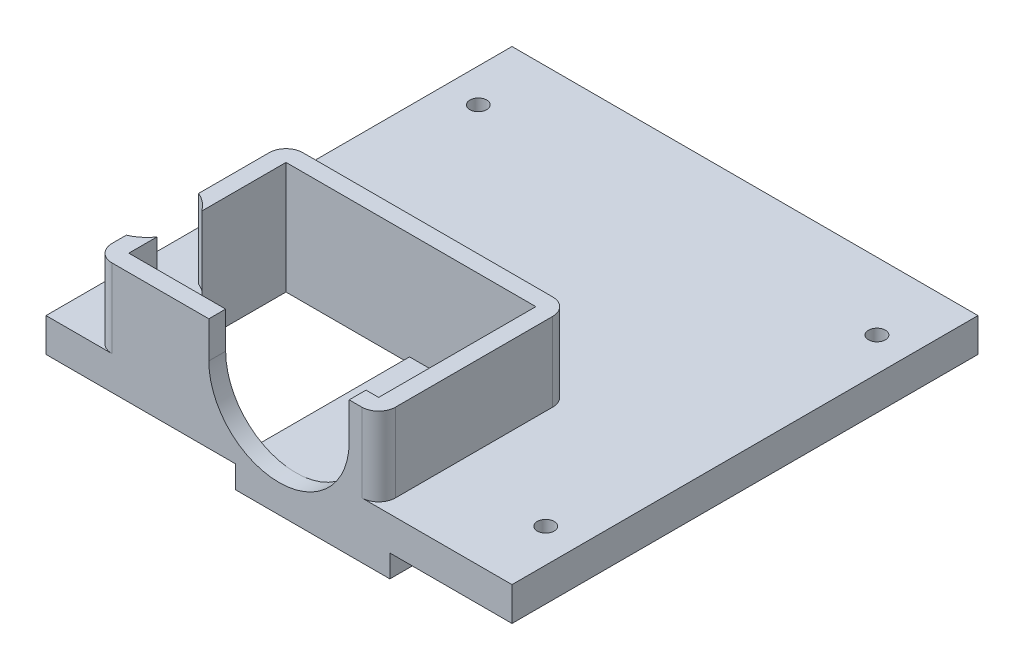
SolidWorks part; units mm, degrees
material "PVB"
ref_plane "Front Plane" through (0, 0, 0) normal (0, 0, 1) x (1, 0, 0)
ref_plane "Top Plane" through (0, 0, 0) normal (0, 1, 0) x (1, 0, 0)
ref_plane "Right Plane" through (0, 0, 0) normal (1, 0, 0) x (0, 0, -1)
sketch "Sketch1" plane through (0, 0, 0) normal (0, 1, 0) x (1, 0, 0)
  line L1 (0, 0) -> (83, 0)
  line L2 (0, 0) -> (0, 83)
  line L3 (0, 83) -> (83, 83)
  line L4 (83, 0) -> (83, 83)
  dimension "D1" = 83
  dimension "D2" = 83
extrude "Boss-Extrude1" add sketch "Sketch1" along normal blind 6
sketch "Sketch2" plane through (0, 6, 0) normal (0, 1, 0) x (1, 0, 0)
  line L0 (83, 83) -> (0, 83) construction
  line L1 (0, 83) -> (0, 0) construction
  line L2 (0, 0) -> (83, 0) construction
  line L3 (83, 0) -> (83, 83) construction
  circle A0 centre (6, 71) radius 1.5
  circle A1 centre (6, 12) radius 1.5
  circle A2 centre (77, 12) radius 1.5
  circle A3 centre (77, 71) radius 1.5
  dimension "D1" = 3
  dimension "D2" = 3
  dimension "D3" = 3
  dimension "D4" = 3
  dimension "D6" = 6
  dimension "D7" = 12
  dimension "D8" = 6
  dimension "D9" = 6
  dimension "D10" = 12
  dimension "D11" = 6
  dimension "D5" = 12
  dimension "D12" = 12
extrude "Cut-Extrude1" cut sketch "Sketch2" against normal through all
ref_plane "Plane1" through (0, 0, -41.5) normal (0, 0, 1) x (1, 0, 0)
sketch "Sketch4" plane through (0, 6, 0) normal (0, 1, 0) x (1, 0, 0)
  line L0 (3, 21) -> (3, 9)
  line L1 (3, 9) -> (13, 9)
  line L2 (13, 15) -> (8, 21)
  line L3 (3, 21) -> (8, 21)
  line L4 (8, 21) -> (13, 15)
  line L5 (13, 15) -> (13, 9)
  line L6 (0, 83) -> (0, 0) construction
  line L7 (0, 0) -> (83, 0) construction
  circle A0 centre (6, 12) radius 1.5
  circle A1 centre (6, 12) radius 1.5 construction
  dimension "D1" = 3
  dimension "D2" = 9
  dimension "D3" = 12
  dimension "D4" = 10
  dimension "D5" = 6
  dimension "D6" = 5
ref_plane "Plane2" through (41.5, 0, 0) normal (-1, 0, 0) x (0, 0, 1)
sketch "Sketch5" plane through (0, 6, 0) normal (0, 1, 0) x (1, 0, 0)
  line L0 (8.75, 34) -> (8.75, 0)
  line L1 (8.75, 34) -> (59.25, 34)
  line L2 (8.75, 0) -> (59.25, 0)
  line L3 (59.25, 34) -> (59.25, 0)
  line L4 (8.75, 34) -> (59.25, 0) construction
  line L5 (8.75, 0) -> (59.25, 34) construction
  line L6 (41.5, 3.3) -> (41.5, -3.3) construction
  line L12 (0, 0) -> (83, 0) construction
  point P1 (34, 17)
  dimension "D1" = 50.5
  dimension "D2" = 34
  dimension "D3" = 7.5
extrude "Boss-Extrude2" add sketch "Sketch5" along normal blind 22
sketch "Sketch6" plane through (0, 28, 0) normal (0, 1, 0) x (1, 0, 0)
  line L14 (56.25, 31) -> (11.75, 31)
  line L15 (11.75, 31) -> (11.75, 3)
  line L16 (11.75, 3) -> (56.25, 3)
  line L17 (56.25, 3) -> (56.25, 31)
  line L18 (56.25, 31) -> (11.75, 31)
  line L19 (11.75, 31) -> (11.75, 3)
  line L20 (11.75, 3) -> (56.25, 3)
  line L21 (56.25, 3) -> (56.25, 31)
  dimension "D1" = 3
extrude "Cut-Extrude5" cut sketch "Sketch6" against normal blind 25
fillet "Fillet1" radius 3 4 edges at (8.75, 17, -34) (59.25, 17, 0) (59.25, 17, -34) (8.75, 17, 0)
sketch "Sketch8" plane through (0, 0, 0) normal (0, 0, 1) x (1, 0, 0)
  line L1 (0, 0) -> (83, 0) construction
  line L3 (59.25, 28) -> (59.25, 6) construction
  circle A0 centre (41.5, 13.5) radius 12.5
  dimension "D2" = 25
  dimension "D1" = 17.75
  dimension "D3" = 13.5
extrude "Cut-Extrude6" cut sketch "Sketch8" against normal blind 10
sketch "Sketch9" plane through (0, 0, 0) normal (0, 0, 1) x (1, 0, 0)
  line L0 (0, 0) -> (83, 0) construction
  line L1 (0, 28) -> (83, 28)
  line L2 (0, 28) -> (0, 20)
  line L3 (0, 20) -> (83, 20)
  line L4 (83, 28) -> (83, 20)
  line L5 (83, 6) -> (83, 0) construction
  line L6 (0, 6) -> (0, 0) construction
  line L7 (11.75, 28) -> (56.25, 28) construction
  dimension "D1" = 20
extrude "Cut-Extrude7" cut sketch "Sketch9" against normal through all both and the other way through all
sketch "Sketch11" plane through (0, 0, 0) normal (0, -1, 0) x (1, 0, 0)
  line L0 (3, -9) -> (13, -9)
  line L1 (13, -9) -> (13, -15)
  line L2 (13, -15) -> (8, -21)
  line L3 (8, -21) -> (3, -21)
  line L4 (3, -21) -> (3, -9)
extrude "Cut-Extrude8" cut sketch "Sketch11" against normal blind 3
mirror "Mirror1" about plane through (0, 0, -41.5) normal (0, 0, 1) of "Cut-Extrude8" second plane through (41.5, 0, 0) second plane normal (-1, 0, 0)
sketch "Sketch13" plane through (0, 20, 0) normal (0, 1, 0) x (1, 0, 0)
  line L12 (52.1771, 0) -> (56.25, 0)
  line L13 (59.25, 3) -> (59.25, 31)
  line L14 (56.25, 34) -> (11.75, 34)
  line L15 (8.75, 31) -> (8.75, 3)
  line L16 (11.75, 0) -> (30.8229, 0)
  line L17 (11.75, 0) -> (30.8229, 0)
  line L18 (30.8229, 0) -> (30.8229, 3)
  line L19 (30.8229, 0) -> (30.8229, 3)
  line L20 (30.8229, 3) -> (11.75, 3)
  line L21 (30.8229, 3) -> (11.75, 3)
  line L22 (11.75, 3) -> (11.75, 31)
  line L23 (11.75, 3) -> (11.75, 31)
  line L24 (52.1771, 0) -> (56.25, 0)
  line L25 (59.25, 3) -> (59.25, 31)
  line L26 (56.25, 34) -> (11.75, 34)
  line L27 (8.75, 31) -> (8.75, 3)
  line L37 (11.75, 31) -> (56.25, 31)
  line L38 (11.75, 31) -> (56.25, 31)
  line L39 (56.25, 31) -> (56.25, 3)
  line L40 (56.25, 31) -> (56.25, 3)
  line L41 (56.25, 3) -> (52.1771, 3)
  line L42 (56.25, 3) -> (52.1771, 3)
  line L43 (52.1771, 3) -> (52.1771, 0)
  line L44 (52.1771, 3) -> (52.1771, 0)
  circle A0 centre (6, 12) radius 1.5 construction
  circle A1 centre (6, 12) radius 1.5
  circle A2 centre (6, 12) radius 7
  arc A11 (56.25, 0) -> (59.25, 3) centre (56.25, 3) ccw
  arc A12 (56.25, 0) -> (59.25, 3) centre (56.25, 3) ccw
  arc A13 (59.25, 31) -> (56.25, 34) centre (56.25, 31) ccw
  arc A14 (59.25, 31) -> (56.25, 34) centre (56.25, 31) ccw
  arc A15 (11.75, 34) -> (8.75, 31) centre (11.75, 31) ccw
  arc A24 (11.75, 34) -> (8.75, 31) centre (11.75, 31) ccw
  arc A25 (8.75, 3) -> (11.75, 0) centre (11.75, 3) ccw
  arc A26 (8.75, 3) -> (11.75, 0) centre (11.75, 3) ccw
  dimension "D2" = 14
  dimension "D1" = 0
extrude "Cut-Extrude9" cut sketch "Sketch13" against normal up to surface (14 mm away) contours L27 A2 L23 up to face at (6, 6, -69.5)
sketch "Sketch14" plane through (0, 0, 0) normal (0, 0, 1) x (1, 0, 0)
  line L0 (29, 13.5) -> (29, 20)
  line L1 (30.8229, 20) -> (11.75, 20) construction
  line L2 (29, 20) -> (30.8229, 20)
  line L3 (30.8229, 20) -> (29, 13.5)
  arc A0 (30.8229, 20) -> (52.1771, 20) centre (41.5, 13.5) ccw construction
extrude "Cut-Extrude10" cut sketch "Sketch14" against normal blind 10
sketch "Sketch15" plane through (0, 0, 0) normal (0, 0, 1) x (1, 0, 0)
  line L0 (54, 20) -> (54, 13.5)
  line L1 (56.25, 20) -> (52.1771, 20) construction
  line L2 (54, 20) -> (52.1771, 20)
  line L3 (52.1771, 20) -> (54, 13.5)
  arc A0 (29, 13.5) -> (52.1771, 20) centre (41.5, 13.5) ccw construction
extrude "Cut-Extrude11" cut sketch "Sketch15" against normal blind 10
sketch "Sketch17" plane through (0, 0, 0) normal (0, -1, 0) x (1, 0, 0)
  line L0 (9.6667, -9) -> (9.6667, -19)
  line L1 (13, -9) -> (3, -9) construction
  line L2 (8, -21) -> (13, -15) construction
  line L3 (9.6667, -19) -> (13, -15)
  line L4 (13, -15) -> (13, -9)
  line L5 (13, -9) -> (9.6667, -9)
  dimension "D1" = 10
extrude "Boss-Extrude3" add sketch "Sketch17" against normal up to surface (3 mm away) up to face at (7.5, 3, -15.3)
sketch "Sketch18" plane through (0, 3, 0) normal (0, 1, 0) x (1, 0, 0)
  line L8 (34.7177, 3) -> (34.7177, 10)
  line L9 (34.7177, 10) -> (48.2823, 10)
  line L10 (48.2823, 10) -> (48.2823, 3)
  line L11 (48.2823, 3) -> (56.25, 3)
  line L12 (56.25, 3) -> (56.25, 31)
  line L13 (56.25, 31) -> (11.75, 31)
  line L14 (11.75, 31) -> (11.75, 3)
  line L15 (11.75, 3) -> (34.7177, 3)
extrude "Cut-Extrude14" cut sketch "Sketch18" against normal blind 4
sketch "Sketch20" plane through (0, 0, 0) normal (0, -1, 0) x (1, 0, 0)
  line L1 (34.7177, -10) -> (48.2823, -10)
  line L2 (34.7177, -10) -> (34.7177, -3)
  line L3 (34.7177, -3) -> (48.2823, -3)
  line L4 (48.2823, -10) -> (48.2823, -3)
extrude "Cut-Extrude15" cut sketch "Sketch20" against normal blind 4
sketch "Sketch21" plane through (0, 0, 0) normal (0, -1, 0) x (1, 0, 0)
  line L0 (0, 0) -> (83, 0) construction
  line L1 (33.75, 0) -> (61.25, 0)
  line L2 (33.75, 0) -> (33.75, -37)
  line L3 (33.75, -37) -> (61.25, -37)
  line L9 (11.75, -31) -> (56.25, -31) construction
  line L10 (11.75, -3) -> (11.75, -31) construction
  line L11 (61.25, 0) -> (61.25, -37)
  line L12 (56.25, -31) -> (56.25, -3) construction
  dimension "D1" = 22
  dimension "D2" = 6
  dimension "D3" = 5
extrude "Boss-Extrude4" add sketch "Sketch21" along normal blind 4 and the other way blind 1
fillet "Fillet2" radius 5 2 edges at (61.25, -2, -37) (33.75, -2, -37)
